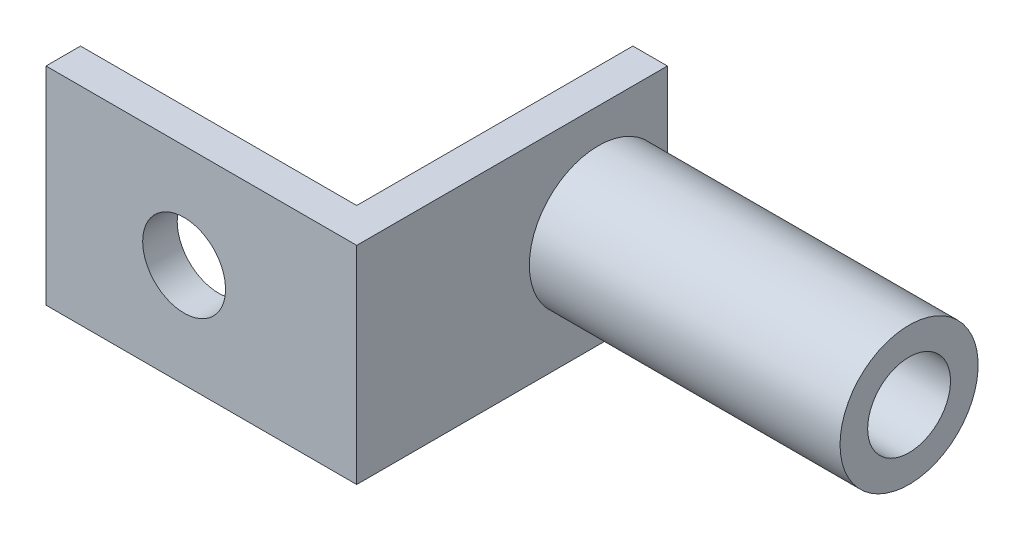
SolidWorks part; units mm, degrees
ref_plane "Front Plane" through (0, 0, 0) normal (0, 0, 1) x (1, 0, 0)
ref_plane "Top Plane" through (0, 0, 0) normal (0, 1, 0) x (1, 0, 0)
ref_plane "Right Plane" through (0, 0, 0) normal (1, 0, 0) x (0, 0, -1)
sketch "Sketch3" plane through (0, 0, 0) normal (0, 1, 0) x (1, 0, 0)
  line L0 (0, 0) -> (22.5, 0)
  line L1 (22.5, 0) -> (22.5, 22.5)
  line L2 (22.5, 22.5) -> (20, 22.5)
  line L3 (20, 22.5) -> (20, 2.5)
  line L4 (20, 2.5) -> (0, 2.5)
  line L5 (0, 2.5) -> (0, 0)
  dimension "D1" = 2.5
  dimension "D2" = 20
extrude "Boss-Extrude2" add sketch "Sketch3" along normal blind 15
sketch "Sketch4" plane through (0, 0, -2.5) normal (0, 0, -1) x (-1, 0, 0)
  line L0 (-20, 15) -> (0, 0) construction
  circle A0 centre (-10, 7.5) radius 3
  dimension "D1" = 6
extrude "Cut-Extrude2" cut sketch "Sketch4" against normal through all
sketch "Sketch7" plane through (20, 0, 0) normal (-1, 0, 0) x (0, 0, 1)
  line L0 (-22.5, 15) -> (-22.5, 0) construction
  line L1 (-22.5, 0) -> (-17.5, 7.5) construction
  line L2 (-17.5, 7.5) -> (-22.5, 15) construction
  circle A0 centre (-17.5, 7.5) radius 5
  circle A1 centre (-17.5, 7.5) radius 3
  dimension "D1" = 10
  dimension "D2" = 6
extrude "Boss-Extrude5" add sketch "Sketch7" against normal blind 25
sketch "Sketch8" plane through (22.5, 0, 0) normal (1, 0, 0) x (0, 0, -1)
  circle A0 centre (17.5, 7.5) radius 3
  circle A1 centre (17.5, 7.5) radius 3 construction
extrude "Cut-Extrude3" cut sketch "Sketch8" against normal through all
equation "\"pulleybolt\"=0.6"
equation "\"D2@Sketch7\"=\"pulleybolt\""
